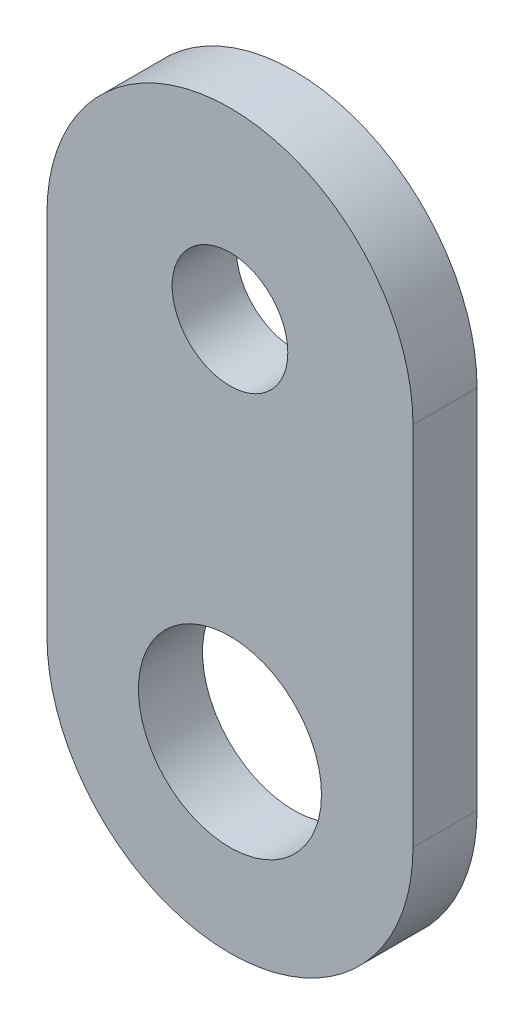
SolidWorks part; units mm, degrees
material "Titanium"
ref_plane "Front Plane" through (0, 0, 0) normal (0, 0, 1) x (1, 0, 0)
ref_plane "Top Plane" through (0, 0, 0) normal (0, 1, 0) x (1, 0, 0)
ref_plane "Right Plane" through (0, 0, 0) normal (1, 0, 0) x (0, 0, -1)
sketch "Sketch1" plane through (0, 0, 0) normal (0, 0, 1) x (1, 0, 0)
  line L0 (0, 0) -> (0, 50.8)
  line L2 (50.8, 50.8) -> (50.8, 0)
  arc A0 (0, 50.8) -> (50.8, 50.8) centre (25.4, 50.8) cw
  arc A1 (50.8, 0) -> (0, 0) centre (25.4, 0) cw
  dimension "D1" = 101.6
  dimension "D2" = 50.8
extrude "Boss-Extrude1" add sketch "Sketch1" along normal blind 8.89
sketch "Sketch2" plane through (0, 0, 8.89) normal (0, 0, 1) x (1, 0, 0)
  line L0 (25.4, 76.2) -> (25.4, -25.4) construction
  line L1 (0, 50.8) -> (50.8, 50.8) construction
  line L2 (0, 0) -> (50.8, 0) construction
  arc A1 (50.8, 50.8) -> (0, 50.8) centre (25.4, 50.8) ccw construction
  arc A2 (0, 0) -> (50.8, 0) centre (25.4, 0) ccw construction
  circle A3 centre (25.4, 0) radius 12.7
  circle A4 centre (25.4, 50.8) radius 8.0264
  dimension "D1" = 16.0528
  dimension "D2" = 25.4
extrude "Cut-Extrude2" cut sketch "Sketch2" against normal through all
equation "\"L\"= 4in"
equation "\"F\"= 650"
equation "\"W\"= 2in"
equation "\"WT\"= 1in"
equation "\"SY\"= 120091"
equation "\"SF\"= 4"
equation "\"T\"= ( \"F\" * \"SF\" ) / ( \"WT\" * \"SY\" )"
equation "\"D1@Sketch1\"= \"L\""
equation "\"D2@Sketch1\"= \"W\""
equation "\"D1@Boss-Extrude1\"=.35"
